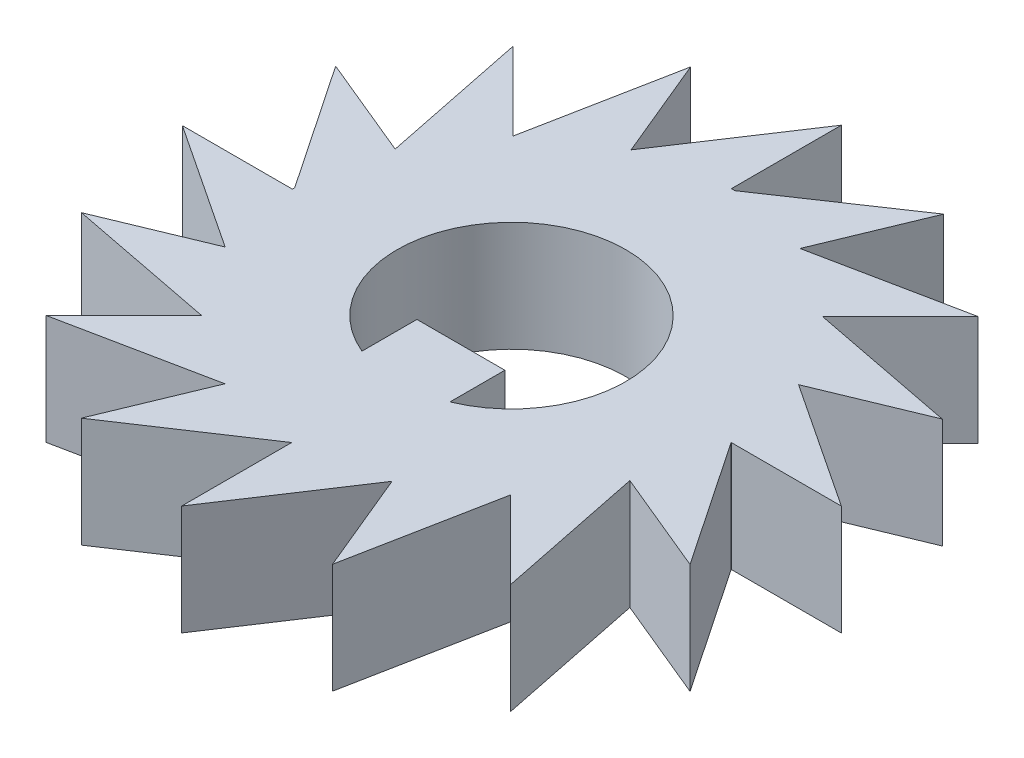
SolidWorks part; units mm, degrees
ref_plane "Front Plane" through (0, 0, 0) normal (0, 0, 1) x (1, 0, 0)
ref_plane "Top Plane" through (0, 0, 0) normal (0, 1, 0) x (1, 0, 0)
ref_plane "Right Plane" through (0, 0, 0) normal (1, 0, 0) x (0, 0, -1)
sketch "Sketch1" plane through (0, 0, 0) normal (0, 1, 0) x (1, 0, 0)
  line L0 (0, -9.9941) -> (0, -14.9941)
  line L1 (0, -14.9941) -> (3.8084, -9.2403)
  line L2 (10, 0) -> (15, 0)
  line L3 (15, 0) -> (9.2465, 3.8082)
  line L4 (0, 10.0002) -> (0, 15.0002)
  line L5 (0, 15.0002) -> (-3.8084, 9.2464)
  line L6 (-9.9639, 0) -> (-14.9639, 0)
  line L7 (-14.9639, 0) -> (-9.2101, -3.8084)
  line L8 (3.8084, -9.2403) -> (5.7218, -13.8597)
  line L9 (5.7218, -13.8597) -> (7.0384, -7.0865)
  line L10 (7.0384, -7.0865) -> (10.5739, -10.622)
  line L11 (10.5739, -10.622) -> (9.1866, -3.8034)
  line L12 (9.1866, -3.8034) -> (13.8584, -5.7385)
  line L13 (13.8584, -5.7385) -> (10, -0.0181)
  line L14 (9.2465, 3.8082) -> (13.8659, 5.7216)
  line L15 (13.8659, 5.7216) -> (7.1065, 7.0355)
  line L16 (7.1065, 7.0355) -> (10.642, 10.571)
  line L17 (10.642, 10.571) -> (3.9141, 9.2022)
  line L18 (3.9141, 9.2022) -> (5.8275, 13.8216)
  line L19 (5.8275, 13.8216) -> (0.1602, 9.999)
  line L20 (-3.8084, 9.2464) -> (-5.7218, 13.8658)
  line L21 (-5.7218, 13.8658) -> (-7.0357, 7.1062)
  line L22 (-7.0357, 7.1062) -> (-10.5712, 10.6418)
  line L23 (-10.5712, 10.6418) -> (-9.2024, 3.9136)
  line L24 (-9.2024, 3.9136) -> (-13.8218, 5.827)
  line L25 (-13.8218, 5.827) -> (-9.9633, 0.1067)
  line L26 (-9.2101, -3.8084) -> (-13.8295, -5.7218)
  line L27 (-13.8295, -5.7218) -> (-7.0563, -7.0384)
  line L28 (-7.0563, -7.0384) -> (-10.5918, -10.5739)
  line L29 (-10.5918, -10.5739) -> (-3.8303, -9.1983)
  line L30 (-3.8303, -9.1983) -> (-5.7437, -13.8177)
  line L32 (-5.7437, -13.8177) -> (0, -9.9941)
  line L33 (0, -5.2) -> (0, 5.2) construction
  line L34 (-2, -4.8) -> (-2, -2.3)
  line L35 (-2, -2.3) -> (2, -2.3)
  line L36 (2, -2.3) -> (2, -4.8)
  arc A1 (2, -4.8) -> (-2, -4.8) centre (0, 0) ccw
  arc A2 (-9.9633, 0.1067) -> (-9.9639, 0) centre (0, 0) ccw
  arc A4 (10, -0.0181) -> (10, 0) centre (0, 0) ccw
  arc A5 (0.1602, 9.999) -> (0, 10.0002) centre (0, 0) ccw
  dimension "D1" = 10.4
  dimension "D3" = 5
  dimension "D4" = 56
  dimension "D5" = 56
  dimension "D6" = 56
  dimension "D7" = 56
  dimension "D8" = 33.5
  dimension "D9" = 33.5
  dimension "D10" = 56
  dimension "D11" = 33.5
  dimension "D12" = 33.5
  dimension "D13" = 56
  dimension "D14" = 33.5
  dimension "D15" = 33.5
  dimension "D16" = 56
  dimension "D17" = 33.5
  dimension "D18" = 33.5
  dimension "D19" = 33.5
  dimension "D20" = 6.9
  dimension "D21" = 6.9
  dimension "D22" = 33.5
  dimension "D23" = 5
  dimension "D24" = 56
  dimension "D25" = 56
  dimension "D26" = 5
  dimension "D27" = 33.5
  dimension "D28" = 5
  dimension "D29" = 56
  dimension "D30" = 33.5
  dimension "D31" = 5
  dimension "D32" = 33.5
  dimension "D33" = 5
  dimension "D34" = 56
  dimension "D35" = 5
  dimension "D36" = 5
  dimension "D37" = 56
  dimension "D38" = 56
  dimension "D39" = 33.5
  dimension "D40" = 5
  dimension "D41" = 6.9
  dimension "D42" = 33.5
  dimension "D43" = 6.9
  dimension "D44" = 6.9
  dimension "D45" = 6.9
  dimension "D46" = 6.9
  dimension "D47" = 6.9
  dimension "D48" = 2
  dimension "D49" = 2
  dimension "D50" = 2.5
extrude "Boss-Extrude1" add sketch "Sketch1" along normal blind 5
